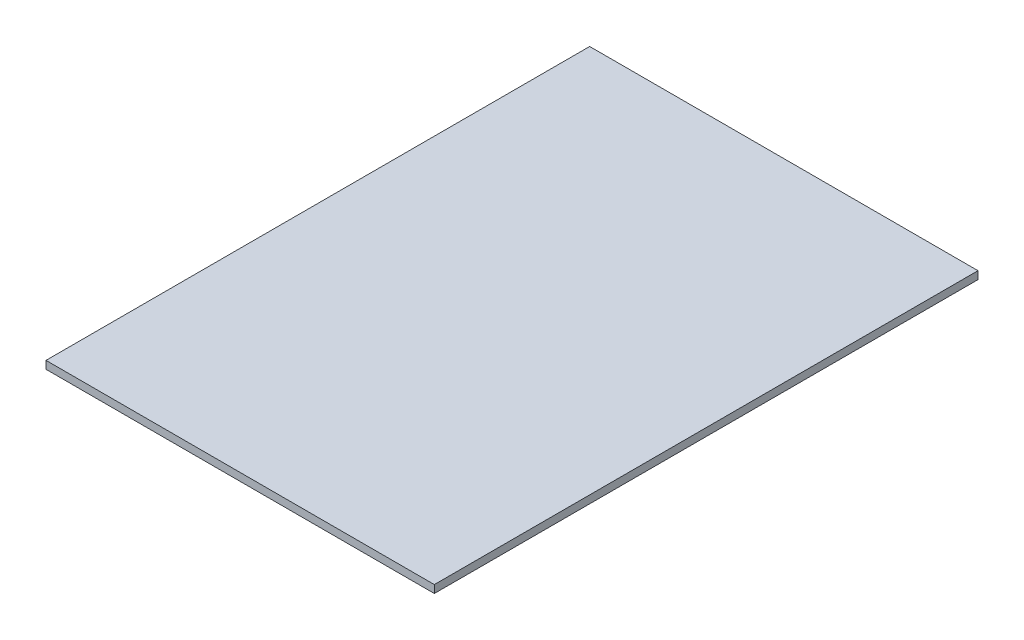
SolidWorks part; units mm, degrees
ref_plane "Front Plane" through (0, 0, 0) normal (0, 0, 1) x (1, 0, 0)
ref_plane "Top Plane" through (0, 0, 0) normal (0, 1, 0) x (1, 0, 0)
ref_plane "Right Plane" through (0, 0, 0) normal (1, 0, 0) x (0, 0, -1)
sketch "Sketch1" plane through (0, 0, 0) normal (0, 1, 0) x (1, 0, 0)
  line L1 (0, 0) -> (250, 0)
  line L2 (0, 0) -> (0, 350)
  line L3 (0, 350) -> (250, 350)
  line L4 (250, 0) -> (250, 350)
  dimension "D1" = 350
  dimension "D2" = 250
extrude "Boss-Extrude1" add sketch "Sketch1" along normal blind 5
